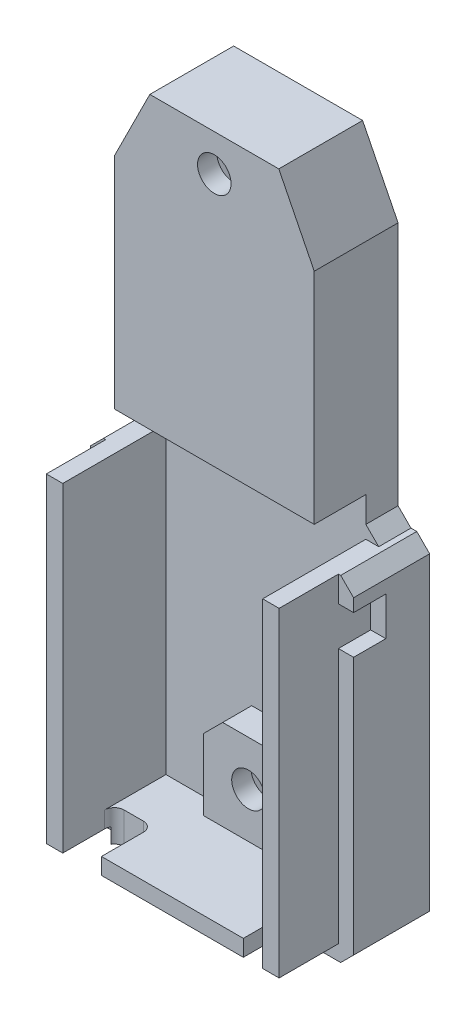
SolidWorks part; units mm, degrees
ref_plane "Front Plane" through (0, 0, 0) normal (0, 0, 1) x (1, 0, 0)
ref_plane "Top Plane" through (0, 0, 0) normal (0, 1, 0) x (1, 0, 0)
ref_plane "Right Plane" through (0, 0, 0) normal (1, 0, 0) x (0, 0, -1)
sketch "Sketch1" plane through (0, 0, 0) normal (0, 0, 1) x (1, 0, 0)
  line L0 (0, -25.75) -> (0, 25.75) construction
  line L1 (-5, 25.75) -> (5, 25.75)
  line L2 (-10.2, 0.25) -> (-10.2, -25.75)
  line L3 (-10.2, -25.75) -> (10.2, -25.75)
  line L4 (10.2, 0.25) -> (10.2, -25.75)
  line L5 (-10.2, 0) -> (0, 0) construction
  line L6 (-7.75, 20.25) -> (-5, 25.75)
  line L7 (-7.75, 20.25) -> (-7.75, 0.25)
  line L8 (-7.75, 0.25) -> (-10.2, 0.25)
  line L9 (7.75, 0.25) -> (10.2, 0.25)
  line L10 (7.75, 20.25) -> (7.75, 0.25)
  line L11 (7.75, 20.25) -> (5, 25.75)
  circle A0 centre (0, 22.9) radius 1.3
  circle A1 centre (0.9, -18.85) radius 1.3
  point P3 (0, 0)
  point P11 (0, 0)
  point P16 (0, 0)
  point P24 (0.9, -18.6)
  dimension "D4" = 2.6
  dimension "D2" = 51.5
  dimension "D3" = 2.85
  dimension "D5" = 0.9
  dimension "D6" = 6.9
  dimension "D7" = 41.75
  dimension "D8" = 5
  dimension "D9" = 5.5
  dimension "D10" = 7.75
  dimension "D11" = 26
  dimension "D13" = 10.2
extrude "Boss-Extrude1" add sketch "Sketch1" along normal blind 2.5
sketch "Sketch2" plane through (0, 0, 2.5) normal (0, 0, 1) x (1, 0, 0)
  line L0 (-7.75, 3.25) -> (7.75, 3.25)
  line L1 (-7.75, 20.25) -> (-7.75, 0.25) construction
  line L2 (7.75, 0.25) -> (7.75, 20.25) construction
  line L3 (7.75, 3.25) -> (7.75, 20.25)
  line L4 (7.75, 20.25) -> (5, 25.75)
  line L5 (5, 25.75) -> (-5, 25.75)
  line L6 (-5, 25.75) -> (-7.75, 20.25)
  line L7 (-5, 25.75) -> (-7.75, 20.25) construction
  line L8 (-7.75, 20.25) -> (-7.75, 3.25)
  line L9 (-7.75, 0.25) -> (-10.2, 0.25) construction
  circle A0 centre (0, 22.9) radius 1.3
  circle A1 centre (0, 22.9) radius 1.3 construction
  dimension "D1" = 3
extrude "Boss-Extrude2" add sketch "Sketch2" along normal blind 4
sketch "Sketch3" plane through (0, 0, 2.5) normal (0, 0, 1) x (1, 0, 0)
  line L0 (0.9, -15.35) -> (0.9, -22.35) construction
  line L1 (-1.1, -15.35) -> (2.9, -15.35)
  line L2 (-2.6, -16.85) -> (-2.6, -22.35)
  line L3 (-2.6, -22.35) -> (4.4, -22.35)
  line L4 (4.4, -16.85) -> (4.4, -22.35)
  line L5 (2.9, -15.35) -> (4.4, -16.85)
  line L6 (-2.6, -16.85) -> (-1.1, -15.35)
  circle A0 centre (0.9, -18.85) radius 1.3 construction
  circle A1 centre (0.9, -18.85) radius 1.3
  point P0 (-2.6, -15.35)
  point P3 (4.4, -15.35)
  point P6 (0.9, -18.85)
  dimension "D1" = 7
  dimension "D2" = 7
extrude "Boss-Extrude3" add sketch "Sketch3" along normal blind 2.25
sketch "Sketch4" plane through (0, 0, 0) normal (0, 0, -1) x (-1, 0, 0)
  line L1 (2.9156, 22.9) -> (1.4578, 25.425)
  line L2 (1.4578, 25.425) -> (-1.4578, 25.425)
  line L3 (-1.4578, 25.425) -> (-2.9156, 22.9)
  line L4 (-2.9156, 22.9) -> (-1.4578, 20.375)
  line L5 (-1.4578, 20.375) -> (1.4578, 20.375)
  line L6 (1.4578, 20.375) -> (2.9156, 22.9)
  circle A0 centre (0, 22.9) radius 2.525 construction
  dimension "D1" = 5.05
extrude "Cut-Extrude1" cut sketch "Sketch4" against normal offset from surface (5 mm away) 1.5 up to face at (0, 16.4167, 6.5)
sketch "Sketch5" plane through (0, 0, 0) normal (0, 0, -1) x (-1, 0, 0)
  line L0 (-1.4578, 20.375) -> (1.4578, 20.375) construction
  line L1 (2.0156, -18.85) -> (0.5578, -16.325)
  line L2 (0.5578, -16.325) -> (-2.3578, -16.325)
  line L3 (-2.3578, -16.325) -> (-3.8156, -18.85)
  line L4 (-3.8156, -18.85) -> (-2.3578, -21.375)
  line L5 (-2.3578, -21.375) -> (0.5578, -21.375)
  line L6 (0.5578, -21.375) -> (2.0156, -18.85)
  circle A0 centre (-0.9, -18.85) radius 2.525 construction
extrude "Cut-Extrude2" cut sketch "Sketch5" against normal offset from surface (3.25 mm away) 1.5 up to face at (0.9, -18.1833, 4.75)
sketch "Sketch6" plane through (0, 0, 2.5) normal (0, 0, 1) x (1, 0, 0)
  line L0 (-7.75, 0.25) -> (-10.2, 0.25)
  line L1 (-10.2, 0.25) -> (-10.2, -25.75)
  line L2 (-10.2, -25.75) -> (10.2, -25.75)
  line L3 (-10.2, -25.75) -> (10.2, -25.75) construction
  line L4 (10.2, -25.75) -> (10.2, 0.25)
  line L5 (10.2, 0.25) -> (7.75, 0.25)
  line L6 (7.75, 0.25) -> (7.75, -23.3)
  line L7 (7.75, -23.3) -> (-7.75, -23.3)
  line L8 (-7.75, -23.3) -> (-7.75, 0.25)
  line L9 (-7.75, -23.3) -> (-7.75, -25.75) construction
  line L11 (-10.2, -23.3) -> (-7.75, -23.3) construction
extrude "Boss-Extrude4" add sketch "Sketch6" along normal blind 8
sketch "Sketch8" plane through (0, -25.75, 0) normal (0, -1, 0) x (1, 0, 0)
  line L0 (-7.75, 10.5) -> (-7.75, 7.25)
  line L1 (-10.2, 10.5) -> (10.2, 10.5) construction
  line L2 (-7.75, 8) -> (-6.25, 8) construction
  line L3 (-4.75, 7.25) -> (-4.75, 10.5)
  line L4 (-6.25, 8) -> (-4.75, 8) construction
  line L5 (6.25, 10.5) -> (6.25, 7.25)
  line L6 (6.25, 7.25) -> (7.75, 7.25) construction
  line L7 (7.75, 7.25) -> (7.75, 10.5)
  line L8 (-7.75, 10.5) -> (-4.75, 10.5)
  line L9 (6.25, 10.5) -> (7.75, 10.5)
  line L10 (-5.5, 6.5) -> (7, 6.5) construction
  line L12 (-7.75, 10.5) -> (-7.75, 2.5) construction
  line L13 (7.75, 10.5) -> (7.75, 2.5) construction
  line L14 (-7, 6.5) -> (-5.5, 6.5)
  arc A0 (-5.5, 6.5) -> (-4.75, 7.25) centre (-5.5, 7.25) ccw
  arc A1 (6.25, 7.25) -> (7.75, 7.25) centre (7, 7.25) ccw
  arc A2 (-7.75, 7.25) -> (-7, 6.5) centre (-7, 7.25) ccw
  dimension "D1" = 4
  dimension "D2" = 1.5
extrude "Cut-Extrude3" cut sketch "Sketch8" against normal up to next
sketch "Sketch9" plane through (0, 0, 10.5) normal (0, 0, 1) x (1, 0, 0)
  line L0 (-8.975, 0.25) -> (-8.975, -24.525) construction
  line L1 (-7.75, 0.25) -> (-10.2, 0.25) construction
  line L2 (-8.975, -24.525) -> (8.975, -24.525) construction
  line L3 (8.975, -24.525) -> (8.975, 0.25) construction
  line L4 (10.2, 0.25) -> (7.75, 0.25) construction
  line L5 (10.2, -24.525) -> (8.975, -24.525) construction
  line L6 (10.2, -25.75) -> (10.2, 0.25) construction
  line L7 (8.975, -24.525) -> (8.975, -25.75) construction
  line L8 (7.75, -25.75) -> (10.2, -25.75) construction
  line L9 (-9.025, 0.25) -> (-10.2, 0.25)
  line L10 (-10.2, 0.25) -> (-10.2, -25.75)
  line L11 (-10.2, -25.75) -> (10.2, -25.75)
  line L12 (10.2, -25.75) -> (10.2, 0.25)
  line L13 (10.2, 0.25) -> (9.025, 0.25)
  line L14 (-9.025, 0.25) -> (-9.025, -24.575)
  line L15 (-9.025, -24.575) -> (9.025, -24.575)
  line L16 (9.025, -24.575) -> (9.025, 0.25)
  dimension "D1" = 0.05
extrude "Cut-Extrude4" cut sketch "Sketch9" against normal blind 4.6
chamfer "Chamfer1" distance 1 angle 45 6 edges at (-10.2, 0.25, 2.95) (-7.75, 0.25, 1.25) (7.75, 0.25, 1.25) (10.2, 0.25, 2.95) (10.2, -25.75, 2.95) (-10.2, -25.75, 2.95)
sketch "Sketch10" plane through (-10.2, 0, 0) normal (-1, 0, 0) x (0, 0, 1)
  line L0 (2.95, -0.75) -> (2.95, -5.35) construction
  line L1 (1.55, -5.35) -> (4.35, -5.35)
  line L2 (1.55, -5.35) -> (1.55, -8.15)
  line L3 (1.55, -8.15) -> (4.35, -8.15)
  line L4 (4.35, -5.35) -> (4.35, -8.15)
  line L5 (1.55, -17.35) -> (4.35, -17.35)
  line L6 (1.55, -17.35) -> (1.55, -20.15)
  line L7 (1.55, -20.15) -> (4.35, -20.15)
  line L8 (4.35, -17.35) -> (4.35, -20.15)
  line L9 (5.9, -12.75) -> (0, -12.75) construction
  line L10 (5.9, -0.75) -> (5.9, -24.75) construction
  line L11 (5.9, -0.75) -> (0, -0.75) construction
  line L12 (0, -0.75) -> (0, -24.75) construction
  line L13 (2.95, -8.15) -> (2.95, -12.75) construction
  line L14 (2.95, -12.75) -> (2.95, -17.35) construction
  line L16 (2.95, -20.15) -> (2.95, -24.75) construction
  line L17 (0, -24.75) -> (5.9, -24.75) construction
  circle A0 centre (2.95, -12.75) radius 2.95 construction
  point P14 (2.95, -17.35)
  dimension "D1" = 2.8
extrude "Cut-Extrude6" cut sketch "Sketch10" against normal offset from surface (1.95 mm away) 0.5 up to face at (-7.75, -15.875, 6.75)
sketch "Sketch12" plane through (0, 0, 5.9) normal (0, 0, 1) x (1, 0, 0)
  line L1 (-10.2, -0.75) -> (-10.2, -24.75) construction
  line L2 (-10.2, -1.75) -> (-9.025, -1.75)
  line L3 (-10.2, -1.75) -> (-10.2, -4.75)
  line L4 (-10.2, -4.75) -> (-9.025, -4.75)
  line L6 (-9.025, -1.75) -> (-9.025, -4.75)
  line L7 (-9.025, -24.575) -> (-9.025, 0.25) construction
  line L8 (9.025, 0.25) -> (9.025, -24.575) construction
  line L9 (9.025, -1.75) -> (10.2, -1.75)
  line L10 (9.025, -1.75) -> (9.025, -4.75)
  line L11 (9.025, -4.75) -> (10.2, -4.75)
  line L12 (10.2, -1.75) -> (10.2, -4.75)
  line L13 (10.2, -24.75) -> (10.2, -0.75) construction
  dimension "D1" = 3
  dimension "D2" = 1
extrude "Cut-Extrude7" cut sketch "Sketch12" against normal blind 2.5
sketch "Sketch13" plane through (0, -24.575, 0) normal (0, -1, 0) x (1, 0, 0)
  line L0 (-7.65, 6.8758) -> (-7.65, 5.9)
  line L1 (-9.2, 5.9) -> (9.2, 5.9) construction
  line L2 (-7.65, 5.9) -> (-4.85, 5.9)
  line L3 (9.025, 5.9) -> (-9.025, 5.9) construction
  line L4 (-7.75, 10.5) -> (-7.75, 7.25) construction
  line L6 (-6.25, 6.5) -> (-6.25, 5.9) construction
  line L7 (-7, 6.5) -> (-5.5, 6.5) construction
  line L8 (-7, 6.5) -> (-5.5, 6.5)
  line L9 (-4.85, 6.8758) -> (-4.85, 5.9)
  line L10 (6.35, 6.8758) -> (6.35, 5.9)
  line L11 (6.35, 5.9) -> (7.65, 5.9)
  line L12 (7, 5.9) -> (7, 6.5) construction
  line L13 (6.25, 10.5) -> (6.25, 7.25) construction
  line L14 (7.65, 6.8758) -> (7.65, 5.9)
  arc A0 (-7.75, 7.25) -> (-7, 6.5) centre (-7, 7.25) ccw construction
  arc A2 (-7.65, 6.8758) -> (-7, 6.5) centre (-7, 7.25) ccw
  arc A3 (-4.85, 6.8758) -> (-5.5, 6.5) centre (-5.5, 7.25) cw
  arc A4 (6.25, 7.25) -> (7.75, 7.25) centre (7, 7.25) ccw construction
  arc A5 (6.35, 6.8758) -> (7.65, 6.8758) centre (7, 7.25) ccw
  dimension "D1" = 0.1
  dimension "D2" = 0.1
extrude "Boss-Extrude6" add sketch "Sketch13" along normal up to surface (1.175 mm away) up to face at (0, -25.75, 2.95)
